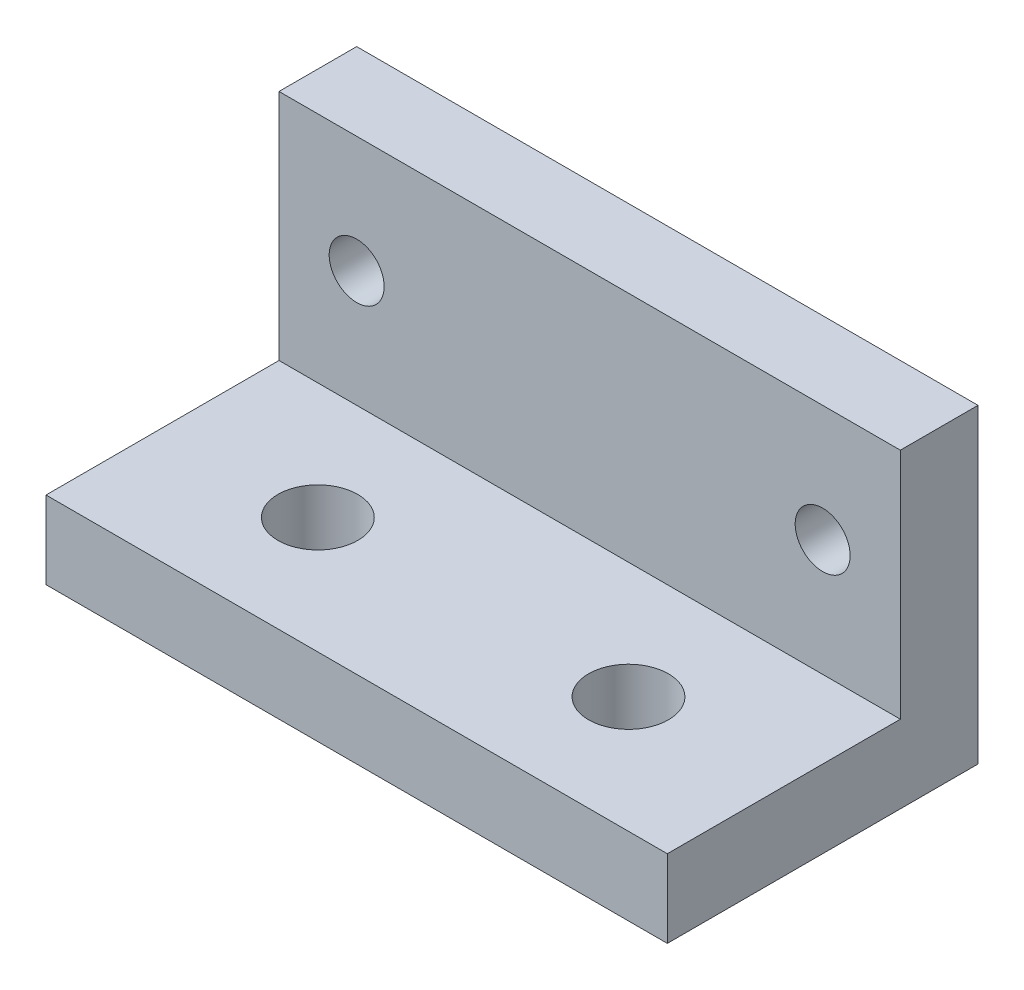
SolidWorks part; units mm, degrees
material "6061-T6 (SS)"
ref_plane "Front Plane" through (0, 0, 0) normal (0, 0, 1) x (1, 0, 0)
ref_plane "Top Plane" through (0, 0, 0) normal (0, 1, 0) x (1, 0, 0)
ref_plane "Right Plane" through (0, 0, 0) normal (1, 0, 0) x (0, 0, -1)
sketch "Sketch1" plane through (0, 0, 0) normal (1, 0, 0) x (0, 0, -1)
  line L0 (0, 0) -> (0, 25.4)
  line L1 (0, 25.4) -> (-6.35, 25.4)
  line L2 (-6.35, 25.4) -> (-6.35, 6.35)
  line L3 (-6.35, 6.35) -> (-25.4, 6.35)
  line L4 (-25.4, 6.35) -> (-25.4, 0)
  line L5 (-25.4, 0) -> (0, 0)
  dimension "D1" = 6.35
  dimension "D2" = 25.4
extrude "Boss-Extrude1" add sketch "Sketch1" along normal mid plane 50.8
hole_wizard "1/4 Clearance Hole1" positions "Sketch3" profile "Sketch2" hole size "1/4" standard "ANSI Inch" end condition up to next
sketch "Sketch3" plane through (0, 6.35, 0) normal (0, 1, 0) x (1, 0, 0)
  line L9 (-25.4, -15.875) -> (25.4, -15.875) construction
  line L13 (-25.4, -15.875) -> (-12.7, -15.875) construction
  line L16 (25.4, -15.875) -> (12.7, -15.875) construction
  line L17 (25.4, -25.4) -> (-25.4, -25.4) construction
  line L18 (25.4, -6.35) -> (25.4, -25.4) construction
  line L19 (-25.4, -6.35) -> (-25.4, -25.4) construction
  point P0 (-12.7, -15.875)
  point P2 (12.7, -15.875)
  dimension "D1" = 25.4
  dimension "D2" = 9.525
sketch "Sketch2" plane through (-12.7, 6.35, 15.875) normal (1, 0, 0) x (0, 0, 1)
  line L0 (0, 0) -> (0, 6.35)
  line L1 (0, 6.35) -> (3.2639, 6.35)
  line L2 (3.2639, 6.35) -> (3.2639, 0)
  line L5 (3.2639, 0) -> (0, 0)
  line L11 (0, -6.35) -> (0, 107.95) construction
  dimension "Thru Hole Dia." = 6.5278
  dimension "Thru Hole Depth" = 6.35
hole_wizard "#8 Clearance Hole1" positions "Sketch5" profile "Sketch4" hole size "#8" standard "ANSI Inch"
sketch "Sketch5" plane through (0, 0, 6.35) normal (0, 0, 1) x (1, 0, 0)
  line L0 (0, 0) -> (0, 50000) construction
  line L1 (25.4, 0) -> (-25.4, 0) construction
  point P0 (-19.05, 15.875)
  point P2 (19.05, 15.875)
  dimension "D1" = 38.1
  dimension "D2" = 15.875
sketch "Sketch4" plane through (-19.05, 15.875, 6.35) normal (1, 0, 0) x (0, -1, 0)
  line L0 (0, 0) -> (0, 7.7007)
  line L1 (0, 7.7007) -> (2.2479, 6.35)
  line L2 (2.2479, 6.35) -> (2.2479, 0)
  line L5 (2.2479, 0) -> (0, 0)
  line L10 (0, 7.7007) -> (-2.2479, 6.35) construction
  line L11 (0, -6.35) -> (0, 107.95) construction
  dimension "Hole Dia." = 4.4958
  dimension "Hole Depth" = 6.35
  dimension "Drill Angle" = 118
equation "\"D2@Sketch3\"=0.3750in"
